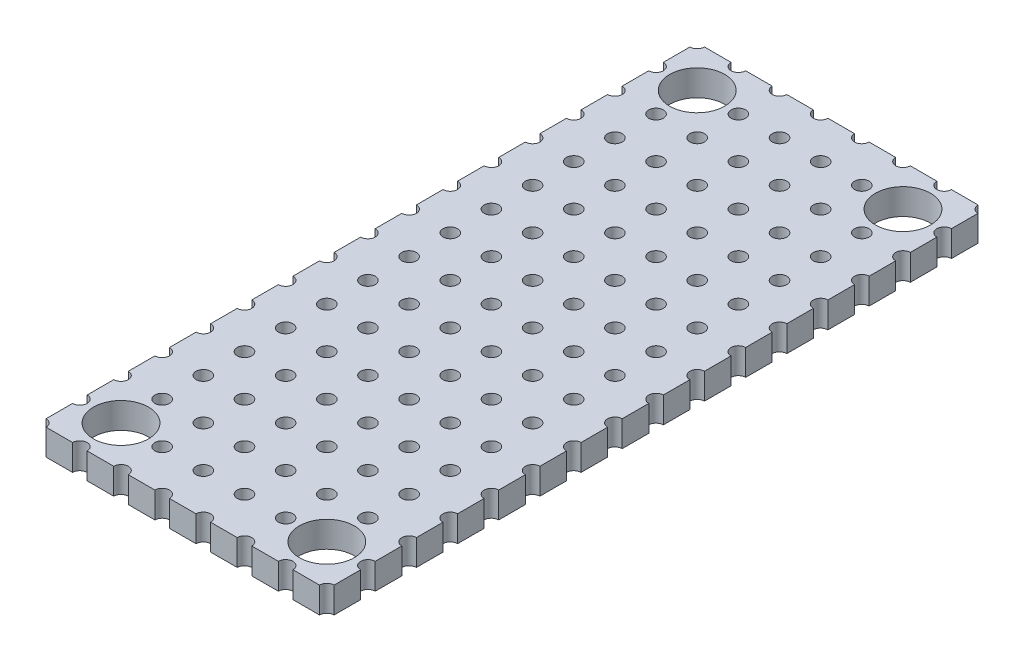
SolidWorks part; units mm, degrees
ref_plane "Plan de face" through (0, 0, 0) normal (0, 0, 1) x (1, 0, 0)
ref_plane "Plan de dessus" through (0, 0, 0) normal (0, 1, 0) x (1, 0, 0)
ref_plane "Plan de droite" through (0, 0, 0) normal (1, 0, 0) x (0, 0, -1)
sketch "Esquisse1" plane through (0, 0, 0) normal (0, 1, 0) x (1, 0, 0)
  line L1 (-3.8847, 3.5299) -> (13.8953, 3.5299)
  line L2 (-3.8847, 3.5299) -> (-3.8847, -37.1101)
  line L3 (-3.8847, -37.1101) -> (13.8953, -37.1101)
  line L4 (13.8953, 3.5299) -> (13.8953, -37.1101)
  dimension "D1" = 17.78
  dimension "D2" = 40.64
extrude "Boss.-Extru.1" add sketch "Esquisse1" along normal blind 1.6
sketch "Esquisse2" plane through (0, 1.6, 0) normal (0, 1, 0) x (1, 0, 0)
  circle A0 centre (-3.8847, 3.5299) radius 0.45
  circle A1 centre (-1.3447, 3.5299) radius 0.45
  circle A2 centre (1.1953, 3.5299) radius 0.45
  circle A3 centre (3.7353, 3.5299) radius 0.45
  circle A4 centre (-1.3447, 0.9899) radius 0.45
  circle A5 centre (1.1953, 0.9899) radius 0.45
  circle A6 centre (3.7353, 0.9899) radius 0.45
  circle A7 centre (-1.3447, -1.5501) radius 0.45
  circle A8 centre (1.1953, -1.5501) radius 0.45
  circle A9 centre (3.7353, -1.5501) radius 0.45
  circle A10 centre (-1.3447, -4.0901) radius 0.45
  circle A11 centre (1.1953, -4.0901) radius 0.45
  circle A12 centre (3.7353, -4.0901) radius 0.45
  circle A13 centre (-1.3447, -6.6301) radius 0.45
  circle A14 centre (1.1953, -6.6301) radius 0.45
  circle A15 centre (3.7353, -6.6301) radius 0.45
  circle A16 centre (-1.3447, -9.1701) radius 0.45
  circle A17 centre (1.1953, -9.1701) radius 0.45
  circle A18 centre (3.7353, -9.1701) radius 0.45
  circle A19 centre (-1.3447, -11.7101) radius 0.45
  circle A20 centre (1.1953, -11.7101) radius 0.45
  circle A21 centre (3.7353, -11.7101) radius 0.45
  circle A22 centre (-1.3447, -14.2501) radius 0.45
  circle A23 centre (1.1953, -14.2501) radius 0.45
  circle A24 centre (3.7353, -14.2501) radius 0.45
  circle A25 centre (-3.8847, 0.9899) radius 0.45
  circle A26 centre (-3.8847, -1.5501) radius 0.45
  circle A27 centre (-3.8847, -4.0901) radius 0.45
  circle A28 centre (-3.8847, -6.6301) radius 0.45
  circle A29 centre (-3.8847, -9.1701) radius 0.45
  circle A30 centre (-3.8847, -11.7101) radius 0.45
  circle A31 centre (-3.8847, -14.2501) radius 0.45
  circle A32 centre (6.2753, 3.5299) radius 0.45
  circle A33 centre (6.2753, 0.9899) radius 0.45
  circle A34 centre (6.2753, -1.5501) radius 0.45
  circle A35 centre (6.2753, -4.0901) radius 0.45
  circle A36 centre (6.2753, -6.6301) radius 0.45
  circle A37 centre (6.2753, -9.1701) radius 0.45
  circle A38 centre (6.2753, -11.7101) radius 0.45
  circle A39 centre (6.2753, -14.2501) radius 0.45
  circle A40 centre (-3.8847, -16.7901) radius 0.45
  circle A41 centre (-1.3447, -16.7901) radius 0.45
  circle A42 centre (1.1953, -16.7901) radius 0.45
  circle A43 centre (3.7353, -16.7901) radius 0.45
  circle A44 centre (6.2753, -16.7901) radius 0.45
  circle A55 centre (8.8153, 3.5299) radius 0.45
  circle A56 centre (11.3553, 3.5299) radius 0.45
  circle A57 centre (13.8953, 3.5299) radius 0.45
  circle A58 centre (16.4353, 3.5299) radius 0.45
  circle A59 centre (18.9753, 3.5299) radius 0.45
  circle A60 centre (8.8153, 0.9899) radius 0.45
  circle A61 centre (11.3553, 0.9899) radius 0.45
  circle A62 centre (13.8953, 0.9899) radius 0.45
  circle A63 centre (16.4353, 0.9899) radius 0.45
  circle A64 centre (18.9753, 0.9899) radius 0.45
  circle A65 centre (8.8153, -1.5501) radius 0.45
  circle A66 centre (11.3553, -1.5501) radius 0.45
  circle A67 centre (13.8953, -1.5501) radius 0.45
  circle A68 centre (16.4353, -1.5501) radius 0.45
  circle A69 centre (18.9753, -1.5501) radius 0.45
  circle A70 centre (8.8153, -4.0901) radius 0.45
  circle A71 centre (11.3553, -4.0901) radius 0.45
  circle A72 centre (13.8953, -4.0901) radius 0.45
  circle A73 centre (16.4353, -4.0901) radius 0.45
  circle A74 centre (18.9753, -4.0901) radius 0.45
  circle A75 centre (8.8153, -6.6301) radius 0.45
  circle A76 centre (11.3553, -6.6301) radius 0.45
  circle A77 centre (13.8953, -6.6301) radius 0.45
  circle A78 centre (16.4353, -6.6301) radius 0.45
  circle A79 centre (18.9753, -6.6301) radius 0.45
  circle A80 centre (8.8153, -9.1701) radius 0.45
  circle A81 centre (11.3553, -9.1701) radius 0.45
  circle A82 centre (13.8953, -9.1701) radius 0.45
  circle A83 centre (16.4353, -9.1701) radius 0.45
  circle A84 centre (18.9753, -9.1701) radius 0.45
  circle A85 centre (8.8153, -11.7101) radius 0.45
  circle A86 centre (11.3553, -11.7101) radius 0.45
  circle A87 centre (13.8953, -11.7101) radius 0.45
  circle A88 centre (16.4353, -11.7101) radius 0.45
  circle A89 centre (18.9753, -11.7101) radius 0.45
  circle A90 centre (8.8153, -14.2501) radius 0.45
  circle A91 centre (11.3553, -14.2501) radius 0.45
  circle A92 centre (13.8953, -14.2501) radius 0.45
  circle A93 centre (16.4353, -14.2501) radius 0.45
  circle A94 centre (18.9753, -14.2501) radius 0.45
  circle A95 centre (8.8153, -16.7901) radius 0.45
  circle A96 centre (11.3553, -16.7901) radius 0.45
  circle A97 centre (13.8953, -16.7901) radius 0.45
  circle A98 centre (16.4353, -16.7901) radius 0.45
  circle A99 centre (18.9753, -16.7901) radius 0.45
  circle A100 centre (-3.8847, -19.3301) radius 0.45
  circle A101 centre (-1.3447, -19.3301) radius 0.45
  circle A102 centre (1.1953, -19.3301) radius 0.45
  circle A103 centre (3.7353, -19.3301) radius 0.45
  circle A104 centre (6.2753, -19.3301) radius 0.45
  circle A105 centre (8.8153, -19.3301) radius 0.45
  circle A106 centre (11.3553, -19.3301) radius 0.45
  circle A107 centre (13.8953, -19.3301) radius 0.45
  circle A108 centre (16.4353, -19.3301) radius 0.45
  circle A109 centre (18.9753, -19.3301) radius 0.45
  circle A110 centre (-3.8847, -21.8701) radius 0.45
  circle A111 centre (-1.3447, -21.8701) radius 0.45
  circle A112 centre (1.1953, -21.8701) radius 0.45
  circle A113 centre (3.7353, -21.8701) radius 0.45
  circle A114 centre (6.2753, -21.8701) radius 0.45
  circle A115 centre (8.8153, -21.8701) radius 0.45
  circle A116 centre (11.3553, -21.8701) radius 0.45
  circle A117 centre (13.8953, -21.8701) radius 0.45
  circle A118 centre (16.4353, -21.8701) radius 0.45
  circle A119 centre (18.9753, -21.8701) radius 0.45
  circle A120 centre (-3.8847, -24.4101) radius 0.45
  circle A121 centre (-1.3447, -24.4101) radius 0.45
  circle A122 centre (1.1953, -24.4101) radius 0.45
  circle A123 centre (3.7353, -24.4101) radius 0.45
  circle A124 centre (6.2753, -24.4101) radius 0.45
  circle A125 centre (8.8153, -24.4101) radius 0.45
  circle A126 centre (11.3553, -24.4101) radius 0.45
  circle A127 centre (13.8953, -24.4101) radius 0.45
  circle A128 centre (16.4353, -24.4101) radius 0.45
  circle A129 centre (18.9753, -24.4101) radius 0.45
  circle A130 centre (-3.8847, -26.9501) radius 0.45
  circle A131 centre (-1.3447, -26.9501) radius 0.45
  circle A132 centre (1.1953, -26.9501) radius 0.45
  circle A133 centre (3.7353, -26.9501) radius 0.45
  circle A134 centre (6.2753, -26.9501) radius 0.45
  circle A135 centre (8.8153, -26.9501) radius 0.45
  circle A136 centre (11.3553, -26.9501) radius 0.45
  circle A137 centre (13.8953, -26.9501) radius 0.45
  circle A138 centre (16.4353, -26.9501) radius 0.45
  circle A139 centre (18.9753, -26.9501) radius 0.45
  circle A140 centre (-3.8847, -29.4901) radius 0.45
  circle A141 centre (-1.3447, -29.4901) radius 0.45
  circle A142 centre (1.1953, -29.4901) radius 0.45
  circle A143 centre (3.7353, -29.4901) radius 0.45
  circle A144 centre (6.2753, -29.4901) radius 0.45
  circle A145 centre (8.8153, -29.4901) radius 0.45
  circle A146 centre (11.3553, -29.4901) radius 0.45
  circle A147 centre (13.8953, -29.4901) radius 0.45
  circle A148 centre (16.4353, -29.4901) radius 0.45
  circle A149 centre (18.9753, -29.4901) radius 0.45
  circle A150 centre (-3.8847, -32.0301) radius 0.45
  circle A151 centre (-1.3447, -32.0301) radius 0.45
  circle A152 centre (1.1953, -32.0301) radius 0.45
  circle A153 centre (3.7353, -32.0301) radius 0.45
  circle A154 centre (6.2753, -32.0301) radius 0.45
  circle A155 centre (8.8153, -32.0301) radius 0.45
  circle A156 centre (11.3553, -32.0301) radius 0.45
  circle A157 centre (13.8953, -32.0301) radius 0.45
  circle A158 centre (16.4353, -32.0301) radius 0.45
  circle A159 centre (18.9753, -32.0301) radius 0.45
  circle A160 centre (-3.8847, -34.5701) radius 0.45
  circle A161 centre (-1.3447, -34.5701) radius 0.45
  circle A162 centre (1.1953, -34.5701) radius 0.45
  circle A163 centre (3.7353, -34.5701) radius 0.45
  circle A164 centre (6.2753, -34.5701) radius 0.45
  circle A165 centre (8.8153, -34.5701) radius 0.45
  circle A166 centre (11.3553, -34.5701) radius 0.45
  circle A167 centre (13.8953, -34.5701) radius 0.45
  circle A168 centre (16.4353, -34.5701) radius 0.45
  circle A169 centre (18.9753, -34.5701) radius 0.45
  circle A170 centre (-3.8847, -37.1101) radius 0.45
  circle A171 centre (-1.3447, -37.1101) radius 0.45
  circle A172 centre (1.1953, -37.1101) radius 0.45
  circle A173 centre (3.7353, -37.1101) radius 0.45
  circle A174 centre (6.2753, -37.1101) radius 0.45
  circle A175 centre (8.8153, -37.1101) radius 0.45
  circle A176 centre (11.3553, -37.1101) radius 0.45
  circle A177 centre (13.8953, -37.1101) radius 0.45
  circle A178 centre (16.4353, -37.1101) radius 0.45
  circle A179 centre (18.9753, -37.1101) radius 0.45
  dimension "D1" = 0.9
  dimension "D4" = 10
  dimension "D5" = 17
extrude "Enlèv. mat.-Extru.1" cut sketch "Esquisse2" against normal through all
hole_wizard "Dégagement M31" positions "Esquisse3" profile "Esquisse4" hole size "M3" standard "ISO" end condition through all
sketch "Esquisse3" plane through (0, 1.6, 0) normal (0, 1, 0) x (1, 0, 0)
  point P0 (11.3553, 0.9899)
  point P8 (-1.3447, 0.9899)
  point P26 (-1.3447, -34.5701)
  point P29 (11.3553, -34.5701)
  point P33 (0, 0)
  point P34 (0, 0)
  point P35 (0, 0)
  point P36 (0, 0)
  point P37 (-1.3447, 0.9899)
  point P39 (11.3553, 0.9899)
  point P41 (-1.3447, -34.5701)
  point P43 (11.3553, -34.5701)
sketch "Esquisse4" plane through (11.3553, 1.6, -0.9899) normal (1, 0, 0) x (0, 0, 1)
  line L0 (0, 0) -> (0, 1.6)
  line L1 (0, 1.6) -> (1.7, 1.6)
  line L2 (1.7, 1.6) -> (1.7, 0)
  line L5 (1.7, 0) -> (0, 0)
  line L11 (0, -6.35) -> (0, 107.95) construction
  dimension "Diamètre du perçage jusqu'au prochain" = 3.4
  dimension "Profondeur du perçage jusqu'au prochain" = 1.6
